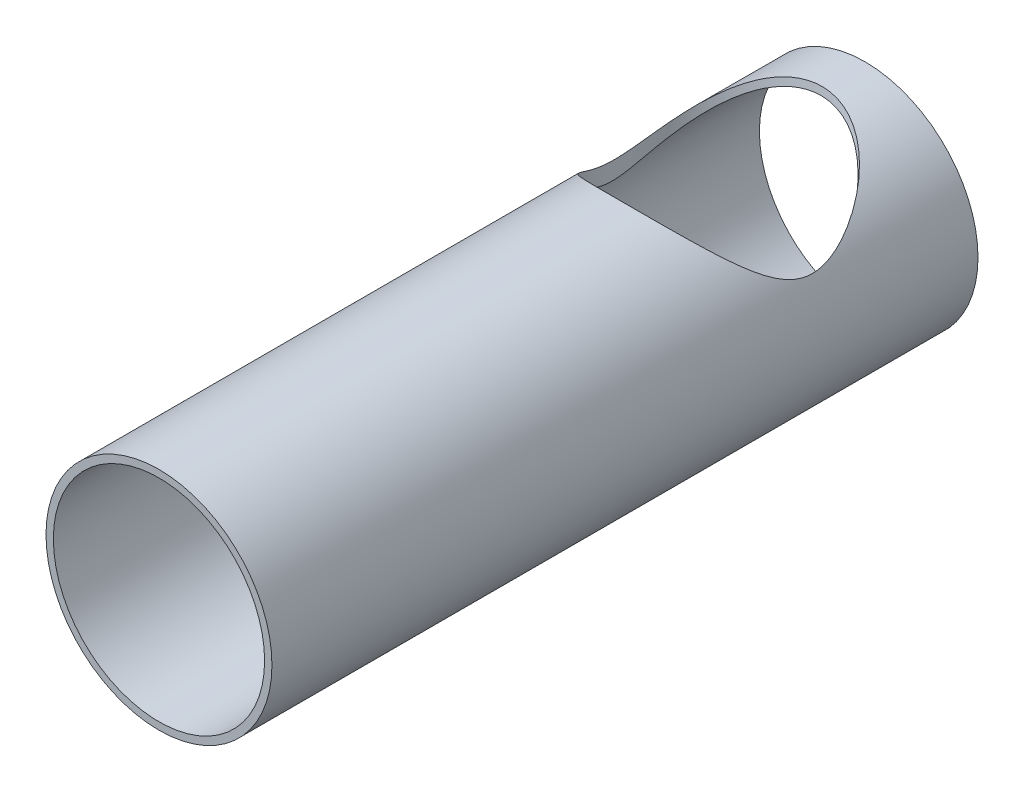
SolidWorks part; units mm, degrees
material "2024-T3"
ref_plane "Front Plane" through (0, 0, 0) normal (0, 0, 1) x (1, 0, 0)
ref_plane "Top Plane" through (0, 0, 0) normal (0, 1, 0) x (1, 0, 0)
ref_plane "Right Plane" through (0, 0, 0) normal (1, 0, 0) x (0, 0, -1)
sketch "Sketch1" plane through (0, 0, 0) normal (0, 0, 1) x (1, 0, 0)
  circle A0 centre (0, 0) radius 23.749
  circle A1 centre (0, 0) radius 25.4
  dimension "D1" = 50.8
  dimension "D2" = 47.498
extrude "Boss-Extrude1" add sketch "Sketch1" along normal blind 158.75
ref_plane "Plane1" through (0, 25.4, 0) normal (0, 1, 0) x (-1, 0, 0)
sketch "Sketch3" plane through (0, 25.4, 0) normal (0, 1, 0) x (-1, 0, 0)
  line L0 (0, 0) -> (37.0572, 0) construction
ref_plane "Plane2" through (0, 24.8451, -3.7131) normal (0, 0.989, -0.1478) x (-1, 0, 0)
sketch "Sketch2" plane through (0, 25.4, 0) normal (0, -0.989, 0.1478) x (-1, 0, 0)
  line L0 (0, 0) -> (37.0572, 0) construction
  circle A0 centre (0, -31.75) radius 22.225
  dimension "D1" = 44.45
  dimension "D2" = 31.75
extrude "Cut-Extrude2" cut sketch "Sketch2" along normal blind 22.86
